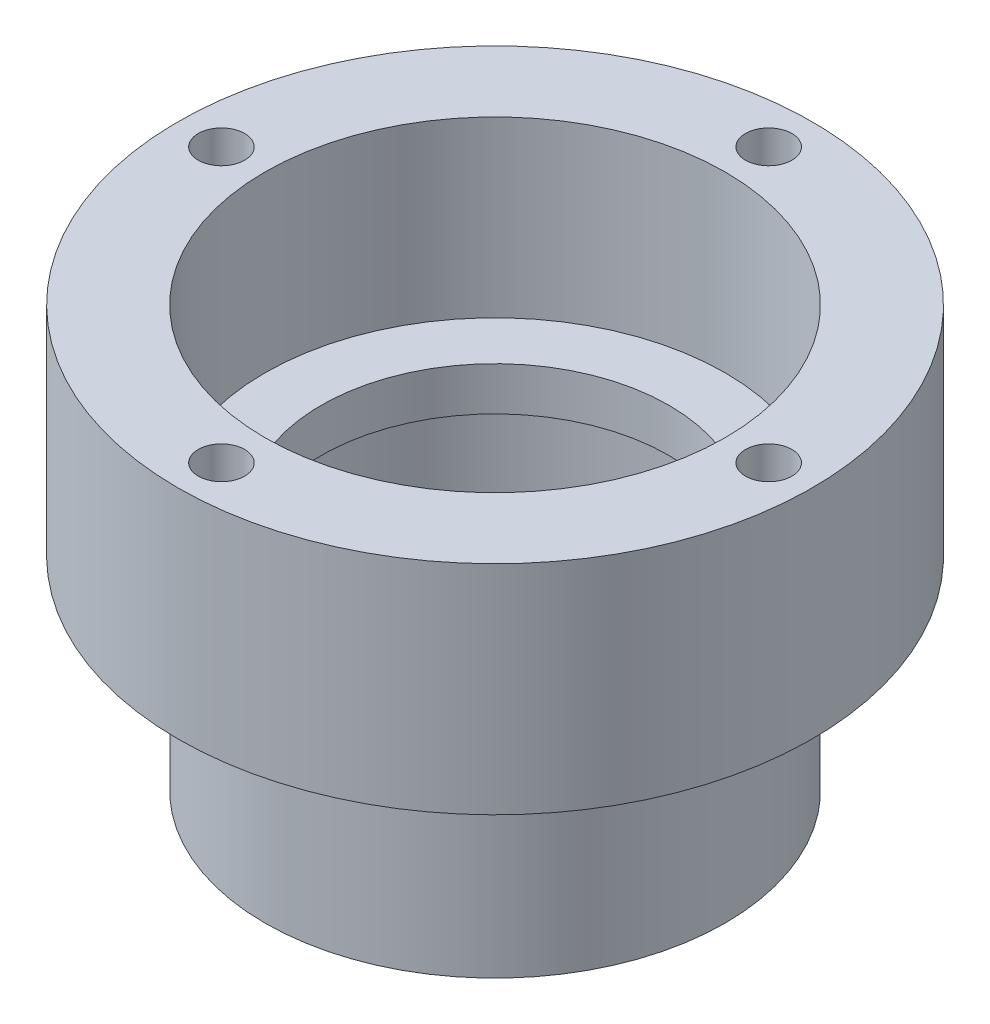
SolidWorks part; units mm, degrees
material "2024 Alloy"
ref_plane "Front Plane" through (0, 0, 0) normal (0, 0, 1) x (1, 0, 0)
ref_plane "Top Plane" through (0, 0, 0) normal (0, 1, 0) x (1, 0, 0)
ref_plane "Right Plane" through (0, 0, 0) normal (1, 0, 0) x (0, 0, -1)
sketch "Sketch1" plane through (0, 0, 0) normal (0, 1, 0) x (1, 0, 0)
  circle A0 centre (0, 0) radius 7.9375
  circle A1 centre (0, 0) radius 6.9375
  dimension "D1" = 15.875
  dimension "D2" = 1
extrude "Boss-Extrude1" add sketch "Sketch1" along normal blind 7
sketch "Sketch2" plane through (0, 7, 0) normal (0, 1, 0) x (1, 0, 0)
  circle A0 centre (0, 0) radius 6
  circle A1 centre (0, 0) radius 7.9375
  circle A2 centre (0, 0) radius 7.9375 construction
  dimension "D1" = 12
extrude "Boss-Extrude2" add sketch "Sketch2" along normal blind 1.5
sketch "Sketch3" plane through (0, 8.5, 0) normal (0, 1, 0) x (1, 0, 0)
  circle A0 centre (0, 0) radius 10.9375
  circle A1 centre (0, 0) radius 7.9375
  circle A4 centre (0, 0) radius 7.9375 construction
  dimension "D1" = 3
  dimension "D2" = 15.875
extrude "Boss-Extrude3" add sketch "Sketch3" along normal blind 6
hole_wizard "M2x0.4 Tapped Hole1" positions "Sketch6" profile "Sketch5" tap size "M2x0.4" standard "ANSI Metric"
sketch "Sketch6" plane through (0, 14.5, 0) normal (0, 1, 0) x (1, 0, 0)
  line L0 (0, 0) -> (9.4375, 0) construction
  line L2 (0, 9.4375) -> (0, 0) construction
  line L4 (-9.4375, 0) -> (0, 0) construction
  line L5 (0, 0) -> (0, -9.4375) construction
  circle A0 centre (0, 0) radius 9.4375
  circle A1 centre (0, 0) radius 10.9375 construction
  point P4 (0, 9.4375)
  point P6 (9.4375, 0)
  point P8 (0, -9.4375)
  point P10 (-9.4375, 0)
  dimension "D1" = 1.5
sketch "Sketch5" plane through (0, 14.5, -9.4375) normal (1, 0, 0) x (0, 0, 1)
  line L0 (0, 0) -> (0, 6.1807)
  line L1 (0, 6.1807) -> (0.8, 5.7)
  line L2 (0.8, 5.7) -> (0.8, 0)
  line L5 (0.8, 0) -> (0, 0)
  line L10 (0, 6.1807) -> (-0.8, 5.7) construction
  line L11 (0, -6.35) -> (0, 107.95) construction
  dimension "Tap Drill Dia." = 1.6
  dimension "Tap Drill Depth" = 5.7
  dimension "Drill Angle" = 118
cosmetic thread "Hole Thread1" parameters "D1"=4.5, "D2"=2
cosmetic thread "Hole Thread2" parameters "D1"=4.5, "D2"=2
cosmetic thread "Hole Thread3" parameters "D1"=4.5, "D2"=2
cosmetic thread "Hole Thread4" parameters "D1"=4.5, "D2"=2
sketch "Sketch7" plane through (0, 8.5, 0) normal (0, -1, 0) x (1, 0, 0)
  circle A0 centre (0, 0) radius 10.9375
  circle A1 centre (0, 0) radius 6.9375
  circle A2 centre (0, 0) radius 10.9375 construction
  circle A3 centre (0, 0) radius 6.9375 construction
extrude "Boss-Extrude4" add sketch "Sketch7" along normal up to surface (1.5 mm away) up to face at (0, 7, 6)
